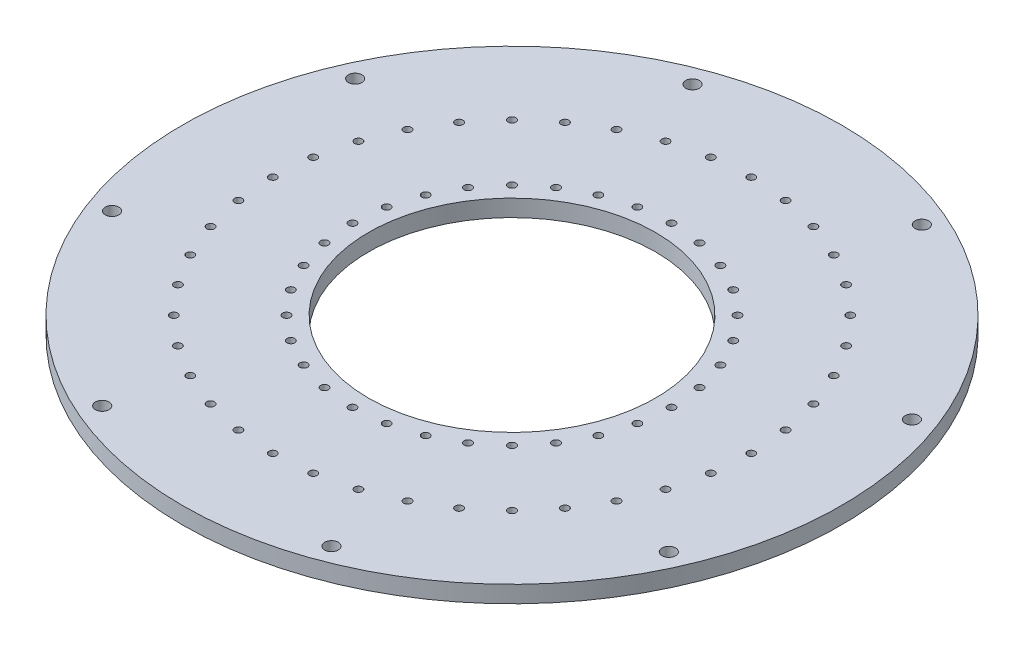
SolidWorks part; units mm, degrees
ref_plane "Front Plane" through (0, 0, 0) normal (0, 0, 1) x (1, 0, 0)
ref_plane "Top Plane" through (0, 0, 0) normal (0, 1, 0) x (1, 0, 0)
ref_plane "Right Plane" through (0, 0, 0) normal (1, 0, 0) x (0, 0, -1)
sketch "Sketch1" plane through (0, 0, 0) normal (0, 1, 0) x (1, 0, 0)
  circle A0 centre (0, 0) radius 124
  dimension "D1" = 248
extrude "Boss-Extrude1" add sketch "Sketch1" along normal blind 6.35
sketch "Sketch5" plane through (0, 0, 0) normal (0, -1, 0) x (1, 0, 0)
  arc A2 (-0.6364, -108.0149) -> (-5.7396, -108.1643) centre (-3.188, -108.0896) ccw
  arc A3 (-5.7396, -108.1643) -> (-0.6364, -108.0149) centre (-3.188, -108.0896) ccw
  arc A4 (-0.6364, -108.0149) -> (-5.7396, -108.1643) centre (-3.188, -108.0896) ccw
  arc A5 (-5.7396, -108.1643) -> (-0.6364, -108.0149) centre (-3.188, -108.0896) ccw
  arc A6 (-13.3309, -108.3866) -> (-18.4341, -108.536) centre (-15.8825, -108.4613) ccw
  arc A7 (-18.4341, -108.536) -> (-13.3309, -108.3866) centre (-15.8825, -108.4613) ccw
  arc A8 (-13.3309, -108.3866) -> (-18.4341, -108.536) centre (-15.8825, -108.4613) ccw
  arc A9 (-18.4341, -108.536) -> (-13.3309, -108.3866) centre (-15.8825, -108.4613) ccw
  arc A10 (-26.0255, -108.7583) -> (-31.1287, -108.9077) centre (-28.5771, -108.833) ccw
  arc A11 (-31.1287, -108.9077) -> (-26.0255, -108.7583) centre (-28.5771, -108.833) ccw
  arc A12 (-26.0255, -108.7583) -> (-31.1287, -108.9077) centre (-28.5771, -108.833) ccw
  arc A13 (-31.1287, -108.9077) -> (-26.0255, -108.7583) centre (-28.5771, -108.833) ccw
  arc A14 (-38.7201, -109.1299) -> (-43.8233, -109.2794) centre (-41.2717, -109.2046) ccw
  arc A15 (-43.8233, -109.2794) -> (-38.7201, -109.1299) centre (-41.2717, -109.2046) ccw
  arc A16 (-38.7201, -109.1299) -> (-43.8233, -109.2794) centre (-41.2717, -109.2046) ccw
  arc A17 (-43.8233, -109.2794) -> (-38.7201, -109.1299) centre (-41.2717, -109.2046) ccw
  arc A18 (-51.7863, -96.8071) -> (-56.8895, -96.9565) centre (-54.3379, -96.8818) ccw
  arc A19 (-56.8895, -96.9565) -> (-51.7863, -96.8071) centre (-54.3379, -96.8818) ccw
  arc A20 (-51.7863, -96.8071) -> (-56.8895, -96.9565) centre (-54.3379, -96.8818) ccw
  arc A21 (-56.8895, -96.9565) -> (-51.7863, -96.8071) centre (-54.3379, -96.8818) ccw
  arc A22 (62.4647, -93.4619) -> (57.3615, -93.6113) centre (59.9131, -93.5366) ccw
  arc A23 (57.3615, -93.6113) -> (62.4647, -93.4619) centre (59.9131, -93.5366) ccw
  arc A24 (62.4647, -93.4619) -> (57.3615, -93.6113) centre (59.9131, -93.5366) ccw
  arc A25 (57.3615, -93.6113) -> (62.4647, -93.4619) centre (59.9131, -93.5366) ccw
  arc A26 (50.1419, -106.5282) -> (45.0387, -106.6776) centre (47.5903, -106.6029) ccw
  arc A27 (45.0387, -106.6776) -> (50.1419, -106.5282) centre (47.5903, -106.6029) ccw
  arc A28 (50.1419, -106.5282) -> (45.0387, -106.6776) centre (47.5903, -106.6029) ccw
  arc A29 (45.0387, -106.6776) -> (50.1419, -106.5282) centre (47.5903, -106.6029) ccw
  arc A30 (37.4473, -106.8998) -> (32.3441, -107.0493) centre (34.8957, -106.9746) ccw
  arc A31 (32.3441, -107.0493) -> (37.4473, -106.8998) centre (34.8957, -106.9746) ccw
  arc A32 (37.4473, -106.8998) -> (32.3441, -107.0493) centre (34.8957, -106.9746) ccw
  arc A33 (32.3441, -107.0493) -> (37.4473, -106.8998) centre (34.8957, -106.9746) ccw
  arc A34 (24.7527, -107.2715) -> (19.6495, -107.4209) centre (22.2011, -107.3462) ccw
  arc A35 (19.6495, -107.4209) -> (24.7527, -107.2715) centre (22.2011, -107.3462) ccw
  arc A36 (24.7527, -107.2715) -> (19.6495, -107.4209) centre (22.2011, -107.3462) ccw
  arc A37 (19.6495, -107.4209) -> (24.7527, -107.2715) centre (22.2011, -107.3462) ccw
  arc A38 (12.0582, -107.6432) -> (6.955, -107.7926) centre (9.5066, -107.7179) ccw
  arc A39 (6.955, -107.7926) -> (12.0582, -107.6432) centre (9.5066, -107.7179) ccw
  arc A40 (12.0582, -107.6432) -> (6.955, -107.7926) centre (9.5066, -107.7179) ccw
  arc A41 (6.955, -107.7926) -> (12.0582, -107.6432) centre (9.5066, -107.7179) ccw
  arc A42 (99.4334, -54.2632) -> (94.3302, -54.4126) centre (96.8818, -54.3379) ccw
  arc A43 (94.3302, -54.4126) -> (99.4334, -54.2632) centre (96.8818, -54.3379) ccw
  arc A44 (99.4334, -54.2632) -> (94.3302, -54.4126) centre (96.8818, -54.3379) ccw
  arc A45 (94.3302, -54.4126) -> (99.4334, -54.2632) centre (96.8818, -54.3379) ccw
  arc A46 (99.8051, -66.9578) -> (94.7018, -67.1072) centre (97.2535, -67.0325) ccw
  arc A47 (94.7018, -67.1072) -> (99.8051, -66.9578) centre (97.2535, -67.0325) ccw
  arc A48 (99.8051, -66.9578) -> (94.7018, -67.1072) centre (97.2535, -67.0325) ccw
  arc A49 (94.7018, -67.1072) -> (99.8051, -66.9578) centre (97.2535, -67.0325) ccw
  arc A50 (87.1105, -67.3294) -> (82.0073, -67.4789) centre (84.5589, -67.4041) ccw
  arc A51 (82.0073, -67.4789) -> (87.1105, -67.3294) centre (84.5589, -67.4041) ccw
  arc A52 (87.1105, -67.3294) -> (82.0073, -67.4789) centre (84.5589, -67.4041) ccw
  arc A53 (82.0073, -67.4789) -> (87.1105, -67.3294) centre (84.5589, -67.4041) ccw
  arc A54 (87.4822, -80.024) -> (82.379, -80.1734) centre (84.9306, -80.0987) ccw
  arc A55 (82.379, -80.1734) -> (87.4822, -80.024) centre (84.9306, -80.0987) ccw
  arc A56 (87.4822, -80.024) -> (82.379, -80.1734) centre (84.9306, -80.0987) ccw
  arc A57 (82.379, -80.1734) -> (87.4822, -80.024) centre (84.9306, -80.0987) ccw
  arc A58 (74.7876, -80.3957) -> (69.6844, -80.5451) centre (72.236, -80.4704) ccw
  arc A59 (69.6844, -80.5451) -> (74.7876, -80.3957) centre (72.236, -80.4704) ccw
  arc A60 (74.7876, -80.3957) -> (69.6844, -80.5451) centre (72.236, -80.4704) ccw
  arc A61 (69.6844, -80.5451) -> (74.7876, -80.3957) centre (72.236, -80.4704) ccw
  arc A62 (75.1593, -93.0902) -> (70.0561, -93.2397) centre (72.6077, -93.1649) ccw
  arc A63 (70.0561, -93.2397) -> (75.1593, -93.0902) centre (72.6077, -93.1649) ccw
  arc A64 (75.1593, -93.0902) -> (70.0561, -93.2397) centre (72.6077, -93.1649) ccw
  arc A65 (70.0561, -93.2397) -> (75.1593, -93.0902) centre (72.6077, -93.1649) ccw
  arc A66 (110.2695, 9.5813) -> (105.1663, 9.4319) centre (107.7179, 9.5066) ccw
  arc A67 (105.1663, 9.4319) -> (110.2695, 9.5813) centre (107.7179, 9.5066) ccw
  arc A68 (110.2695, 9.5813) -> (105.1663, 9.4319) centre (107.7179, 9.5066) ccw
  arc A69 (105.1663, 9.4319) -> (110.2695, 9.5813) centre (107.7179, 9.5066) ccw
  arc A70 (110.6412, -3.1133) -> (105.538, -3.2627) centre (108.0896, -3.188) ccw
  arc A71 (105.538, -3.2627) -> (110.6412, -3.1133) centre (108.0896, -3.188) ccw
  arc A72 (110.6412, -3.1133) -> (105.538, -3.2627) centre (108.0896, -3.188) ccw
  arc A73 (105.538, -3.2627) -> (110.6412, -3.1133) centre (108.0896, -3.188) ccw
  arc A74 (105.9097, -15.9572) -> (111.0129, -15.8078) centre (108.4613, -15.8825) ccw
  arc A75 (111.0129, -15.8078) -> (105.9097, -15.9572) centre (108.4613, -15.8825) ccw
  arc A76 (105.9097, -15.9572) -> (111.0129, -15.8078) centre (108.4613, -15.8825) ccw
  arc A77 (111.0129, -15.8078) -> (105.9097, -15.9572) centre (108.4613, -15.8825) ccw
  arc A78 (111.3846, -28.5024) -> (106.2814, -28.6518) centre (108.833, -28.5771) ccw
  arc A79 (106.2814, -28.6518) -> (111.3846, -28.5024) centre (108.833, -28.5771) ccw
  arc A80 (111.3846, -28.5024) -> (106.2814, -28.6518) centre (108.833, -28.5771) ccw
  arc A81 (106.2814, -28.6518) -> (111.3846, -28.5024) centre (108.833, -28.5771) ccw
  arc A82 (111.7563, -41.1969) -> (106.653, -41.3464) centre (109.2046, -41.2717) ccw
  arc A83 (106.653, -41.3464) -> (111.7563, -41.1969) centre (109.2046, -41.2717) ccw
  arc A84 (111.7563, -41.1969) -> (106.653, -41.3464) centre (109.2046, -41.2717) ccw
  arc A85 (106.653, -41.3464) -> (111.7563, -41.1969) centre (109.2046, -41.2717) ccw
  arc A86 (95.7166, 72.6824) -> (90.6133, 72.533) centre (93.1649, 72.6077) ccw
  arc A87 (90.6133, 72.533) -> (95.7166, 72.6824) centre (93.1649, 72.6077) ccw
  arc A88 (95.7166, 72.6824) -> (90.6133, 72.533) centre (93.1649, 72.6077) ccw
  arc A89 (90.6133, 72.533) -> (95.7166, 72.6824) centre (93.1649, 72.6077) ccw
  arc A90 (96.0882, 59.9878) -> (90.985, 59.8384) centre (93.5366, 59.9131) ccw
  arc A91 (90.985, 59.8384) -> (96.0882, 59.9878) centre (93.5366, 59.9131) ccw
  arc A92 (96.0882, 59.9878) -> (90.985, 59.8384) centre (93.5366, 59.9131) ccw
  arc A93 (90.985, 59.8384) -> (96.0882, 59.9878) centre (93.5366, 59.9131) ccw
  arc A94 (109.1545, 47.665) -> (104.0513, 47.5156) centre (106.6029, 47.5903) ccw
  arc A95 (104.0513, 47.5156) -> (109.1545, 47.665) centre (106.6029, 47.5903) ccw
  arc A96 (109.1545, 47.665) -> (104.0513, 47.5156) centre (106.6029, 47.5903) ccw
  arc A97 (104.0513, 47.5156) -> (109.1545, 47.665) centre (106.6029, 47.5903) ccw
  arc A98 (109.5262, 34.9704) -> (104.4229, 34.821) centre (106.9746, 34.8957) ccw
  arc A99 (104.4229, 34.821) -> (109.5262, 34.9704) centre (106.9746, 34.8957) ccw
  arc A100 (109.5262, 34.9704) -> (104.4229, 34.821) centre (106.9746, 34.8957) ccw
  arc A101 (104.4229, 34.821) -> (109.5262, 34.9704) centre (106.9746, 34.8957) ccw
  arc A102 (109.8978, 22.2758) -> (104.7946, 22.1264) centre (107.3462, 22.2011) ccw
  arc A103 (104.7946, 22.1264) -> (109.8978, 22.2758) centre (107.3462, 22.2011) ccw
  arc A104 (109.8978, 22.2758) -> (104.7946, 22.1264) centre (107.3462, 22.2011) ccw
  arc A105 (104.7946, 22.1264) -> (109.8978, 22.2758) centre (107.3462, 22.2011) ccw
  arc A106 (43.8233, 109.2794) -> (38.7201, 109.1299) centre (41.2717, 109.2046) ccw
  arc A107 (38.7201, 109.1299) -> (43.8233, 109.2794) centre (41.2717, 109.2046) ccw
  arc A108 (43.8233, 109.2794) -> (38.7201, 109.1299) centre (41.2717, 109.2046) ccw
  arc A109 (38.7201, 109.1299) -> (43.8233, 109.2794) centre (41.2717, 109.2046) ccw
  arc A110 (56.8895, 96.9565) -> (51.7863, 96.8071) centre (54.3379, 96.8818) ccw
  arc A111 (51.7863, 96.8071) -> (56.8895, 96.9565) centre (54.3379, 96.8818) ccw
  arc A112 (56.8895, 96.9565) -> (51.7863, 96.8071) centre (54.3379, 96.8818) ccw
  arc A113 (51.7863, 96.8071) -> (56.8895, 96.9565) centre (54.3379, 96.8818) ccw
  arc A114 (69.9557, 84.6336) -> (64.8525, 84.4842) centre (67.4041, 84.5589) ccw
  arc A115 (64.8525, 84.4842) -> (69.9557, 84.6336) centre (67.4041, 84.5589) ccw
  arc A116 (69.9557, 84.6336) -> (64.8525, 84.4842) centre (67.4041, 84.5589) ccw
  arc A117 (64.8525, 84.4842) -> (69.9557, 84.6336) centre (67.4041, 84.5589) ccw
  arc A118 (69.5841, 97.3282) -> (64.4809, 97.1787) centre (67.0325, 97.2535) ccw
  arc A119 (64.4809, 97.1787) -> (69.5841, 97.3282) centre (67.0325, 97.2535) ccw
  arc A120 (69.5841, 97.3282) -> (64.4809, 97.1787) centre (67.0325, 97.2535) ccw
  arc A121 (64.4809, 97.1787) -> (69.5841, 97.3282) centre (67.0325, 97.2535) ccw
  arc A122 (82.6503, 85.0053) -> (77.5471, 84.8559) centre (80.0987, 84.9306) ccw
  arc A123 (77.5471, 84.8559) -> (82.6503, 85.0053) centre (80.0987, 84.9306) ccw
  arc A124 (82.6503, 85.0053) -> (77.5471, 84.8559) centre (80.0987, 84.9306) ccw
  arc A125 (77.5471, 84.8559) -> (82.6503, 85.0053) centre (80.0987, 84.9306) ccw
  arc A126 (83.022, 72.3107) -> (77.9188, 72.1613) centre (80.4704, 72.236) ccw
  arc A127 (77.9188, 72.1613) -> (83.022, 72.3107) centre (80.4704, 72.236) ccw
  arc A128 (83.022, 72.3107) -> (77.9188, 72.1613) centre (80.4704, 72.236) ccw
  arc A129 (77.9188, 72.1613) -> (83.022, 72.3107) centre (80.4704, 72.236) ccw
  arc A130 (-19.6495, 107.4209) -> (-24.7527, 107.2715) centre (-22.2011, 107.3462) ccw
  arc A131 (-24.7527, 107.2715) -> (-19.6495, 107.4209) centre (-22.2011, 107.3462) ccw
  arc A132 (-19.6495, 107.4209) -> (-24.7527, 107.2715) centre (-22.2011, 107.3462) ccw
  arc A133 (-24.7527, 107.2715) -> (-19.6495, 107.4209) centre (-22.2011, 107.3462) ccw
  arc A134 (-12.0582, 107.6432) -> (-6.955, 107.7926) centre (-9.5066, 107.7179) ccw
  arc A135 (-6.955, 107.7926) -> (-12.0582, 107.6432) centre (-9.5066, 107.7179) ccw
  arc A136 (-12.0582, 107.6432) -> (-6.955, 107.7926) centre (-9.5066, 107.7179) ccw
  arc A137 (-6.955, 107.7926) -> (-12.0582, 107.6432) centre (-9.5066, 107.7179) ccw
  arc A138 (5.7396, 108.1643) -> (0.6364, 108.0149) centre (3.188, 108.0896) ccw
  arc A139 (0.6364, 108.0149) -> (5.7396, 108.1643) centre (3.188, 108.0896) ccw
  arc A140 (5.7396, 108.1643) -> (0.6364, 108.0149) centre (3.188, 108.0896) ccw
  arc A141 (0.6364, 108.0149) -> (5.7396, 108.1643) centre (3.188, 108.0896) ccw
  arc A142 (18.4341, 108.536) -> (13.3309, 108.3866) centre (15.8825, 108.4613) ccw
  arc A143 (13.3309, 108.3866) -> (18.4341, 108.536) centre (15.8825, 108.4613) ccw
  arc A144 (18.4341, 108.536) -> (13.3309, 108.3866) centre (15.8825, 108.4613) ccw
  arc A145 (13.3309, 108.3866) -> (18.4341, 108.536) centre (15.8825, 108.4613) ccw
  arc A146 (31.1287, 108.9077) -> (26.0255, 108.7583) centre (28.5771, 108.833) ccw
  arc A147 (26.0255, 108.7583) -> (31.1287, 108.9077) centre (28.5771, 108.833) ccw
  arc A148 (31.1287, 108.9077) -> (26.0255, 108.7583) centre (28.5771, 108.833) ccw
  arc A149 (26.0255, 108.7583) -> (31.1287, 108.9077) centre (28.5771, 108.833) ccw
  arc A150 (-69.6844, 80.5451) -> (-74.7876, 80.3957) centre (-72.236, 80.4704) ccw
  arc A151 (-74.7876, 80.3957) -> (-69.6844, 80.5451) centre (-72.236, 80.4704) ccw
  arc A152 (-69.6844, 80.5451) -> (-74.7876, 80.3957) centre (-72.236, 80.4704) ccw
  arc A153 (-74.7876, 80.3957) -> (-69.6844, 80.5451) centre (-72.236, 80.4704) ccw
  arc A154 (-70.0561, 93.2397) -> (-75.1593, 93.0902) centre (-72.6077, 93.1649) ccw
  arc A155 (-75.1593, 93.0902) -> (-70.0561, 93.2397) centre (-72.6077, 93.1649) ccw
  arc A156 (-70.0561, 93.2397) -> (-75.1593, 93.0902) centre (-72.6077, 93.1649) ccw
  arc A157 (-75.1593, 93.0902) -> (-70.0561, 93.2397) centre (-72.6077, 93.1649) ccw
  arc A158 (-57.3615, 93.6113) -> (-62.4647, 93.4619) centre (-59.9131, 93.5366) ccw
  arc A159 (-62.4647, 93.4619) -> (-57.3615, 93.6113) centre (-59.9131, 93.5366) ccw
  arc A160 (-57.3615, 93.6113) -> (-62.4647, 93.4619) centre (-59.9131, 93.5366) ccw
  arc A161 (-62.4647, 93.4619) -> (-57.3615, 93.6113) centre (-59.9131, 93.5366) ccw
  arc A162 (-45.0387, 106.6776) -> (-50.1419, 106.5282) centre (-47.5903, 106.6029) ccw
  arc A163 (-50.1419, 106.5282) -> (-45.0387, 106.6776) centre (-47.5903, 106.6029) ccw
  arc A164 (-45.0387, 106.6776) -> (-50.1419, 106.5282) centre (-47.5903, 106.6029) ccw
  arc A165 (-50.1419, 106.5282) -> (-45.0387, 106.6776) centre (-47.5903, 106.6029) ccw
  arc A166 (-32.3441, 107.0493) -> (-37.4473, 106.8998) centre (-34.8957, 106.9746) ccw
  arc A167 (-37.4473, 106.8998) -> (-32.3441, 107.0493) centre (-34.8957, 106.9746) ccw
  arc A168 (-32.3441, 107.0493) -> (-37.4473, 106.8998) centre (-34.8957, 106.9746) ccw
  arc A169 (-37.4473, 106.8998) -> (-32.3441, 107.0493) centre (-34.8957, 106.9746) ccw
  arc A170 (-106.2814, 28.6518) -> (-111.3846, 28.5024) centre (-108.833, 28.5771) ccw
  arc A171 (-111.3846, 28.5024) -> (-106.2814, 28.6518) centre (-108.833, 28.5771) ccw
  arc A172 (-106.2814, 28.6518) -> (-111.3846, 28.5024) centre (-108.833, 28.5771) ccw
  arc A173 (-111.3846, 28.5024) -> (-106.2814, 28.6518) centre (-108.833, 28.5771) ccw
  arc A174 (-106.653, 41.3464) -> (-111.7563, 41.1969) centre (-109.2046, 41.2717) ccw
  arc A175 (-111.7563, 41.1969) -> (-106.653, 41.3464) centre (-109.2046, 41.2717) ccw
  arc A176 (-106.653, 41.3464) -> (-111.7563, 41.1969) centre (-109.2046, 41.2717) ccw
  arc A177 (-111.7563, 41.1969) -> (-106.653, 41.3464) centre (-109.2046, 41.2717) ccw
  arc A178 (-94.3302, 54.4126) -> (-99.4334, 54.2632) centre (-96.8818, 54.3379) ccw
  arc A179 (-99.4334, 54.2632) -> (-94.3302, 54.4126) centre (-96.8818, 54.3379) ccw
  arc A180 (-94.3302, 54.4126) -> (-99.4334, 54.2632) centre (-96.8818, 54.3379) ccw
  arc A181 (-99.4334, 54.2632) -> (-94.3302, 54.4126) centre (-96.8818, 54.3379) ccw
  arc A182 (-94.7018, 67.1072) -> (-99.8051, 66.9578) centre (-97.2535, 67.0325) ccw
  arc A183 (-99.8051, 66.9578) -> (-94.7018, 67.1072) centre (-97.2535, 67.0325) ccw
  arc A184 (-94.7018, 67.1072) -> (-99.8051, 66.9578) centre (-97.2535, 67.0325) ccw
  arc A185 (-99.8051, 66.9578) -> (-94.7018, 67.1072) centre (-97.2535, 67.0325) ccw
  arc A186 (-82.0073, 67.4789) -> (-87.1105, 67.3294) centre (-84.5589, 67.4041) ccw
  arc A187 (-87.1105, 67.3294) -> (-82.0073, 67.4789) centre (-84.5589, 67.4041) ccw
  arc A188 (-82.0073, 67.4789) -> (-87.1105, 67.3294) centre (-84.5589, 67.4041) ccw
  arc A189 (-87.1105, 67.3294) -> (-82.0073, 67.4789) centre (-84.5589, 67.4041) ccw
  arc A190 (-82.379, 80.1734) -> (-87.4822, 80.024) centre (-84.9306, 80.0987) ccw
  arc A191 (-87.4822, 80.024) -> (-82.379, 80.1734) centre (-84.9306, 80.0987) ccw
  arc A192 (-82.379, 80.1734) -> (-87.4822, 80.024) centre (-84.9306, 80.0987) ccw
  arc A193 (-87.4822, 80.024) -> (-82.379, 80.1734) centre (-84.9306, 80.0987) ccw
  arc A194 (-104.4229, -34.821) -> (-109.5262, -34.9704) centre (-106.9746, -34.8957) ccw
  arc A195 (-109.5262, -34.9704) -> (-104.4229, -34.821) centre (-106.9746, -34.8957) ccw
  arc A196 (-104.4229, -34.821) -> (-109.5262, -34.9704) centre (-106.9746, -34.8957) ccw
  arc A197 (-109.5262, -34.9704) -> (-104.4229, -34.821) centre (-106.9746, -34.8957) ccw
  arc A198 (-104.7946, -22.1264) -> (-109.8978, -22.2758) centre (-107.3462, -22.2011) ccw
  arc A199 (-109.8978, -22.2758) -> (-104.7946, -22.1264) centre (-107.3462, -22.2011) ccw
  arc A200 (-104.7946, -22.1264) -> (-109.8978, -22.2758) centre (-107.3462, -22.2011) ccw
  arc A201 (-109.8978, -22.2758) -> (-104.7946, -22.1264) centre (-107.3462, -22.2011) ccw
  arc A202 (-105.1663, -9.4319) -> (-110.2695, -9.5813) centre (-107.7179, -9.5066) ccw
  arc A203 (-110.2695, -9.5813) -> (-105.1663, -9.4319) centre (-107.7179, -9.5066) ccw
  arc A204 (-105.1663, -9.4319) -> (-110.2695, -9.5813) centre (-107.7179, -9.5066) ccw
  arc A205 (-110.2695, -9.5813) -> (-105.1663, -9.4319) centre (-107.7179, -9.5066) ccw
  arc A206 (-105.538, 3.2627) -> (-110.6412, 3.1133) centre (-108.0896, 3.188) ccw
  arc A207 (-110.6412, 3.1133) -> (-105.538, 3.2627) centre (-108.0896, 3.188) ccw
  arc A208 (-105.538, 3.2627) -> (-110.6412, 3.1133) centre (-108.0896, 3.188) ccw
  arc A209 (-110.6412, 3.1133) -> (-105.538, 3.2627) centre (-108.0896, 3.188) ccw
  arc A210 (-105.9097, 15.9572) -> (-111.0129, 15.8078) centre (-108.4613, 15.8825) ccw
  arc A211 (-111.0129, 15.8078) -> (-105.9097, 15.9572) centre (-108.4613, 15.8825) ccw
  arc A212 (-105.9097, 15.9572) -> (-111.0129, 15.8078) centre (-108.4613, 15.8825) ccw
  arc A213 (-111.0129, 15.8078) -> (-105.9097, 15.9572) centre (-108.4613, 15.8825) ccw
  arc A214 (-77.5471, -84.8559) -> (-82.6503, -85.0053) centre (-80.0987, -84.9306) ccw
  arc A215 (-82.6503, -85.0053) -> (-77.5471, -84.8559) centre (-80.0987, -84.9306) ccw
  arc A216 (-77.5471, -84.8559) -> (-82.6503, -85.0053) centre (-80.0987, -84.9306) ccw
  arc A217 (-82.6503, -85.0053) -> (-77.5471, -84.8559) centre (-80.0987, -84.9306) ccw
  arc A218 (-77.9188, -72.1613) -> (-83.022, -72.3107) centre (-80.4704, -72.236) ccw
  arc A219 (-83.022, -72.3107) -> (-77.9188, -72.1613) centre (-80.4704, -72.236) ccw
  arc A220 (-77.9188, -72.1613) -> (-83.022, -72.3107) centre (-80.4704, -72.236) ccw
  arc A221 (-83.022, -72.3107) -> (-77.9188, -72.1613) centre (-80.4704, -72.236) ccw
  arc A222 (-95.7166, -72.6824) -> (-90.6133, -72.533) centre (-93.1649, -72.6077) ccw
  arc A223 (-90.6133, -72.533) -> (-95.7166, -72.6824) centre (-93.1649, -72.6077) ccw
  arc A224 (-95.7166, -72.6824) -> (-90.6133, -72.533) centre (-93.1649, -72.6077) ccw
  arc A225 (-90.6133, -72.533) -> (-95.7166, -72.6824) centre (-93.1649, -72.6077) ccw
  arc A226 (-90.985, -59.8384) -> (-96.0882, -59.9878) centre (-93.5366, -59.9131) ccw
  arc A227 (-96.0882, -59.9878) -> (-90.985, -59.8384) centre (-93.5366, -59.9131) ccw
  arc A228 (-90.985, -59.8384) -> (-96.0882, -59.9878) centre (-93.5366, -59.9131) ccw
  arc A229 (-96.0882, -59.9878) -> (-90.985, -59.8384) centre (-93.5366, -59.9131) ccw
  arc A230 (-104.0513, -47.5156) -> (-109.1545, -47.665) centre (-106.6029, -47.5903) ccw
  arc A231 (-109.1545, -47.665) -> (-104.0513, -47.5156) centre (-106.6029, -47.5903) ccw
  arc A232 (-104.0513, -47.5156) -> (-109.1545, -47.665) centre (-106.6029, -47.5903) ccw
  arc A233 (-109.1545, -47.665) -> (-104.0513, -47.5156) centre (-106.6029, -47.5903) ccw
  arc A234 (-69.5841, -97.3282) -> (-64.4809, -97.1787) centre (-67.0325, -97.2535) ccw
  arc A235 (-64.4809, -97.1787) -> (-69.5841, -97.3282) centre (-67.0325, -97.2535) ccw
  arc A236 (-69.5841, -97.3282) -> (-64.4809, -97.1787) centre (-67.0325, -97.2535) ccw
  arc A237 (-64.4809, -97.1787) -> (-69.5841, -97.3282) centre (-67.0325, -97.2535) ccw
  arc A238 (-64.8525, -84.4842) -> (-69.9557, -84.6336) centre (-67.4041, -84.5589) ccw
  arc A239 (-69.9557, -84.6336) -> (-64.8525, -84.4842) centre (-67.4041, -84.5589) ccw
  arc A240 (-64.8525, -84.4842) -> (-69.9557, -84.6336) centre (-67.4041, -84.5589) ccw
  arc A241 (-69.9557, -84.6336) -> (-64.8525, -84.4842) centre (-67.4041, -84.5589) ccw
  dimension "D1" = 0
  dimension "D2" = 0
  dimension "D3" = 0
  dimension "D4" = 0
  dimension "D5" = 0
  dimension "D6" = 0
  dimension "D7" = 0
  dimension "D8" = 0
  dimension "D9" = 0
  dimension "D10" = 0
  dimension "D11" = 0
  dimension "D12" = 0
  dimension "D13" = 0
  dimension "D14" = 0
  dimension "D15" = 0
  dimension "D16" = 0
  dimension "D17" = 0
  dimension "D18" = 0
  dimension "D19" = 0
  dimension "D20" = 0
  dimension "D21" = 0
  dimension "D22" = 0
  dimension "D23" = 0
  dimension "D24" = 0
  dimension "D25" = 0
  dimension "D26" = 0
  dimension "D27" = 0
  dimension "D28" = 0
  dimension "D29" = 0
  dimension "D30" = 0
  dimension "D31" = 0
  dimension "D32" = 0
  dimension "D33" = 0
  dimension "D34" = 0
  dimension "D35" = 0
  dimension "D36" = 0
  dimension "D37" = 0
  dimension "D38" = 0
  dimension "D39" = 0
  dimension "D40" = 0
  dimension "D41" = 0
  dimension "D42" = 0
  dimension "D43" = 0
  dimension "D44" = 0
  dimension "D45" = 0
  dimension "D46" = 0
  dimension "D47" = 0
  dimension "D48" = 0
  dimension "D49" = 0
  dimension "D50" = 0
  dimension "D51" = 0
  dimension "D52" = 0
  dimension "D53" = 0
  dimension "D54" = 0
  dimension "D55" = 0
  dimension "D56" = 0
  dimension "D57" = 0
  dimension "D58" = 0
  dimension "D59" = 0
  dimension "D60" = 0
sketch "Sketch6" plane through (0, 0, 0) normal (0, -1, 0) x (1, 0, 0)
  circle A0 centre (-109.2046, 41.2717) radius 2.5527
  circle A1 centre (-106.6029, -47.5903) radius 2.5527
  circle A2 centre (109.2046, -41.2717) radius 2.5527
  circle A3 centre (106.6029, 47.5903) radius 2.5527
  circle A4 centre (41.2717, 109.2046) radius 2.5527
  circle A5 centre (-47.5903, 106.6029) radius 2.5527
  circle A6 centre (-41.2717, -109.2046) radius 2.5527
  circle A7 centre (47.5903, -106.6029) radius 2.5527
extrude "Cut-Extrude1" cut sketch "Sketch6" against normal through all
sketch "Sketch8" plane through (0, 6.35, 0) normal (0, 1, 0) x (1, 0, 0)
  circle A0 centre (0, 0) radius 11
  dimension "D1" = 22
extrude "Cut-Extrude3" cut sketch "Sketch8" against normal through all
sketch "Sketch9" plane through (0, 6.35, 0) normal (0, 1, 0) x (1, 0, 0)
  line L0 (0, 0) -> (0, 17.45) construction
  line L1 (0, 0) -> (-15.1121, -8.725) construction
  line L2 (0, 0) -> (15.1121, -8.725) construction
  circle A0 centre (0, 0) radius 17.45 construction
  circle A1 centre (-15.1121, -8.725) radius 2.45
  circle A2 centre (0, 17.45) radius 2.45
  circle A3 centre (15.1121, -8.725) radius 2.45
  dimension "D1" = 34.9
  dimension "D4" = 4.9
  dimension "D2" = 120
  dimension "D3" = 120
extrude "Cut-Extrude4" cut sketch "Sketch9" against normal through all
sketch "Sketch10" plane through (0, 6.35, 0) normal (0, 1, 0) x (1, 0, 0)
  line L0 (-124, 0) -> (124, 0) construction
  line L1 (0, -124) -> (0, 124) construction
  line L2 (-124, 124) -> (124, 124) construction
  line L3 (-124, -124) -> (124, -124) construction
  line L4 (-124, 124) -> (-124, -124) construction
  line L5 (124, -124) -> (124, 124) construction
  circle A0 centre (0, 0) radius 124 construction
  point P10 (0, 124)
  point P13 (0, -124)
sketch "Sketch11" plane through (0, 0, 0) normal (0, 0, 1) x (1, 0, 0)
  line L0 (0, 6.35) -> (0, 246.35) construction
  line L1 (11, 6.35) -> (-11, 6.35) construction
  circle A0 centre (0, 246.35) radius 15.5372
  dimension "D1" = 240
sketch "Sketch12" plane through (0, 6.35, 0) normal (0, 1, 0) x (1, 0, 0)
  line L0 (0, 0) -> (0, 30) construction
  line L1 (0, 30) -> (0, 60) construction
  line L2 (0, 60) -> (0, 90) construction
  circle A0 centre (0, 30) radius 1.45
  circle A1 centre (0, 60) radius 1.45
  circle A2 centre (0, 90) radius 1.45
  circle A3 centre (0, 0) radius 30 construction
  circle A4 centre (0, 0) radius 60 construction
  circle A5 centre (0, 0) radius 90 construction
  circle A6 centre (11.4805, 27.7164) radius 1.45
  circle A7 centre (21.2132, 21.2132) radius 1.45
  circle A8 centre (27.7164, 11.4805) radius 1.45
  circle A9 centre (30, 0) radius 1.45
  circle A10 centre (27.7164, -11.4805) radius 1.45
  circle A11 centre (21.2132, -21.2132) radius 1.45
  circle A12 centre (11.4805, -27.7164) radius 1.45
  circle A13 centre (0, -30) radius 1.45
  circle A14 centre (-11.4805, -27.7164) radius 1.45
  circle A15 centre (-21.2132, -21.2132) radius 1.45
  circle A16 centre (-27.7164, -11.4805) radius 1.45
  circle A17 centre (-30, 0) radius 1.45
  circle A18 centre (-27.7164, 11.4805) radius 1.45
  circle A19 centre (-21.2132, 21.2132) radius 1.45
  circle A20 centre (-11.4805, 27.7164) radius 1.45
  circle A21 centre (11.7054, 58.8471) radius 1.45
  circle A22 centre (22.961, 55.4328) radius 1.45
  circle A23 centre (33.3342, 49.8882) radius 1.45
  circle A24 centre (42.4264, 42.4264) radius 1.45
  circle A25 centre (49.8882, 33.3342) radius 1.45
  circle A26 centre (55.4328, 22.961) radius 1.45
  circle A27 centre (58.8471, 11.7054) radius 1.45
  circle A28 centre (60, 0) radius 1.45
  circle A29 centre (58.8471, -11.7054) radius 1.45
  circle A30 centre (55.4328, -22.961) radius 1.45
  circle A31 centre (49.8882, -33.3342) radius 1.45
  circle A32 centre (42.4264, -42.4264) radius 1.45
  circle A33 centre (33.3342, -49.8882) radius 1.45
  circle A34 centre (22.961, -55.4328) radius 1.45
  circle A35 centre (11.7054, -58.8471) radius 1.45
  circle A36 centre (0, -60) radius 1.45
  circle A37 centre (-11.7054, -58.8471) radius 1.45
  circle A38 centre (-22.961, -55.4328) radius 1.45
  circle A39 centre (-33.3342, -49.8882) radius 1.45
  circle A40 centre (-42.4264, -42.4264) radius 1.45
  circle A41 centre (-49.8882, -33.3342) radius 1.45
  circle A42 centre (-55.4328, -22.961) radius 1.45
  circle A43 centre (-58.8471, -11.7054) radius 1.45
  circle A44 centre (-60, 0) radius 1.45
  circle A45 centre (-58.8471, 11.7054) radius 1.45
  circle A46 centre (-55.4328, 22.961) radius 1.45
  circle A47 centre (-49.8882, 33.3342) radius 1.45
  circle A48 centre (-42.4264, 42.4264) radius 1.45
  circle A49 centre (-33.3342, 49.8882) radius 1.45
  circle A50 centre (-22.961, 55.4328) radius 1.45
  circle A51 centre (-11.7054, 58.8471) radius 1.45
  circle A52 centre (14.0791, 88.892) radius 1.45
  circle A53 centre (27.8115, 85.5951) radius 1.45
  circle A54 centre (40.8591, 80.1906) radius 1.45
  circle A55 centre (52.9007, 72.8115) radius 1.45
  circle A56 centre (63.6396, 63.6396) radius 1.45
  circle A57 centre (72.8115, 52.9007) radius 1.45
  circle A58 centre (80.1906, 40.8591) radius 1.45
  circle A59 centre (85.5951, 27.8115) radius 1.45
  circle A60 centre (88.892, 14.0791) radius 1.45
  circle A61 centre (90, 0) radius 1.45
  circle A62 centre (88.892, -14.0791) radius 1.45
  circle A63 centre (85.5951, -27.8115) radius 1.45
  circle A64 centre (80.1906, -40.8591) radius 1.45
  circle A65 centre (72.8115, -52.9007) radius 1.45
  circle A66 centre (63.6396, -63.6396) radius 1.45
  circle A67 centre (52.9007, -72.8115) radius 1.45
  circle A68 centre (40.8591, -80.1906) radius 1.45
  circle A69 centre (27.8115, -85.5951) radius 1.45
  circle A70 centre (14.0791, -88.892) radius 1.45
  circle A71 centre (0, -90) radius 1.45
  circle A72 centre (-14.0791, -88.892) radius 1.45
  circle A73 centre (-27.8115, -85.5951) radius 1.45
  circle A74 centre (-40.8591, -80.1906) radius 1.45
  circle A75 centre (-52.9007, -72.8115) radius 1.45
  circle A76 centre (-63.6396, -63.6396) radius 1.45
  circle A77 centre (-72.8115, -52.9007) radius 1.45
  circle A78 centre (-80.1906, -40.8591) radius 1.45
  circle A79 centre (-85.5951, -27.8115) radius 1.45
  circle A80 centre (-88.892, -14.0791) radius 1.45
  circle A81 centre (-90, 0) radius 1.45
  circle A82 centre (-88.892, 14.0791) radius 1.45
  circle A83 centre (-85.5951, 27.8115) radius 1.45
  circle A84 centre (-80.1906, 40.8591) radius 1.45
  circle A85 centre (-72.8115, 52.9007) radius 1.45
  circle A86 centre (-63.6396, 63.6396) radius 1.45
  circle A87 centre (-52.9007, 72.8115) radius 1.45
  circle A88 centre (-40.8591, 80.1906) radius 1.45
  circle A89 centre (-27.8115, 85.5951) radius 1.45
  circle A90 centre (-14.0791, 88.892) radius 1.45
  point P43 (0, 0)
  point P106 (0, 0)
  point P186 (0, 0)
  dimension "D4" = 2.9
  dimension "D1" = 30
  dimension "D2" = 30
  dimension "D3" = 30
  dimension "D5" = 16
  dimension "D6" = 32
  dimension "D7" = 40
extrude "Cut-Extrude5" cut sketch "Sketch12" against normal through all
sketch "Sketch13" plane through (0, 6.35, 0) normal (0, 1, 0) x (1, 0, 0)
  line L0 (0, 60) -> (0, 54) construction
  circle A0 centre (0, 0) radius 54
  dimension "D1" = 6
extrude "Cut-Extrude6" cut sketch "Sketch13" against normal through all
sketch "Sketch14" plane through (0, 6.35, 0) normal (0, 1, 0) x (1, 0, 0)
  line L0 (-90, 0) -> (-88.892, 14.0791) construction
  line L1 (90, 0) -> (88.892, -14.0791) construction
  line L2 (89.446, -7.0396) -> (-89.446, 7.0396) construction
  line L3 (0, 0) -> (7.0396, 89.446) construction
  line L4 (0, 90) -> (14.0791, 88.892) construction
  point P17 (0, 0)
ref_plane "Plane1" through (0, 16.35, 0) normal (0, 1, 0) x (1, 0, 0)
sketch "Sketch15" plane through (0, 16.35, 0) normal (0, 1, 0) x (1, 0, 0)
  line L0 (-90, 0) -> (-88.892, 14.0791) construction
  line L1 (0, 90) -> (14.0791, 88.892) construction
  line L2 (0, 0) -> (7.0396, 89.446) construction
  line L3 (90, 0) -> (88.892, -14.0791) construction
  line L4 (89.446, -7.0396) -> (-89.446, 7.0396) construction
  line L5 (-90, 0) -> (-88.892, 14.0791) construction
  line L6 (0, 90) -> (14.0791, 88.892) construction
  line L7 (0, 0) -> (7.0396, 89.446) construction
  line L8 (90, 0) -> (88.892, -14.0791) construction
  line L9 (89.446, -7.0396) -> (-89.446, 7.0396) construction
ref_plane "Plane2" through (-89.446, 0, -7.0396) normal (0.9969, 0, 0.0785) x (0.0785, 0, -0.9969)
ref_plane "Plane3" through (89.446, 0, 7.0396) normal (-0.9969, 0, -0.0785) x (-0.0785, 0, 0.9969)
sketch "Sketch16" plane through (0, 6.35, 0) normal (0, 1, 0) x (1, 0, 0)
  line L0 (0, 0) -> (50.5775, 0) construction
  line L1 (89.446, -7.0396) -> (-89.446, 7.0396) construction
  line L2 (0, 0) -> (70.7662, -5.5694) construction
ref_plane "Plane4" through (0, 0, 0) normal (0.9969, 0, 0.0785) x (0.0785, 0, -0.9969)
